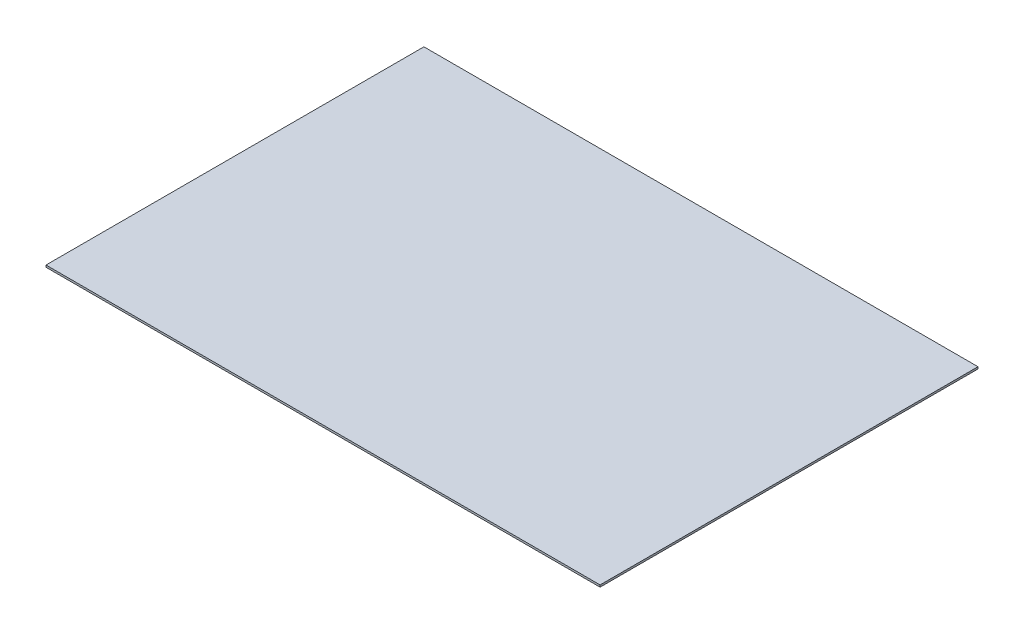
SolidWorks part; units mm, degrees
ref_plane "Front Plane" through (0, 0, 0) normal (0, 0, 1) x (1, 0, 0)
ref_plane "Top Plane" through (0, 0, 0) normal (0, 1, 0) x (1, 0, 0)
ref_plane "Right Plane" through (0, 0, 0) normal (1, 0, 0) x (0, 0, -1)
sketch "Sketch1" plane through (0, 0, 0) normal (0, 1, 0) x (1, 0, 0)
  line L1 (-893.7625, -609.6) -> (893.7625, -609.6)
  line L2 (-893.7625, -609.6) -> (-893.7625, 609.6)
  line L3 (-893.7625, 609.6) -> (893.7625, 609.6)
  line L4 (893.7625, -609.6) -> (893.7625, 609.6)
  line L5 (-893.7625, -609.6) -> (893.7625, 609.6) construction
  line L6 (-893.7625, 609.6) -> (893.7625, -609.6) construction
  point P0 (0, 0)
  dimension "D1" = 1787.525
  dimension "D2" = 1219.2
extrude "Boss-Extrude1" add sketch "Sketch1" along normal blind 6.35
